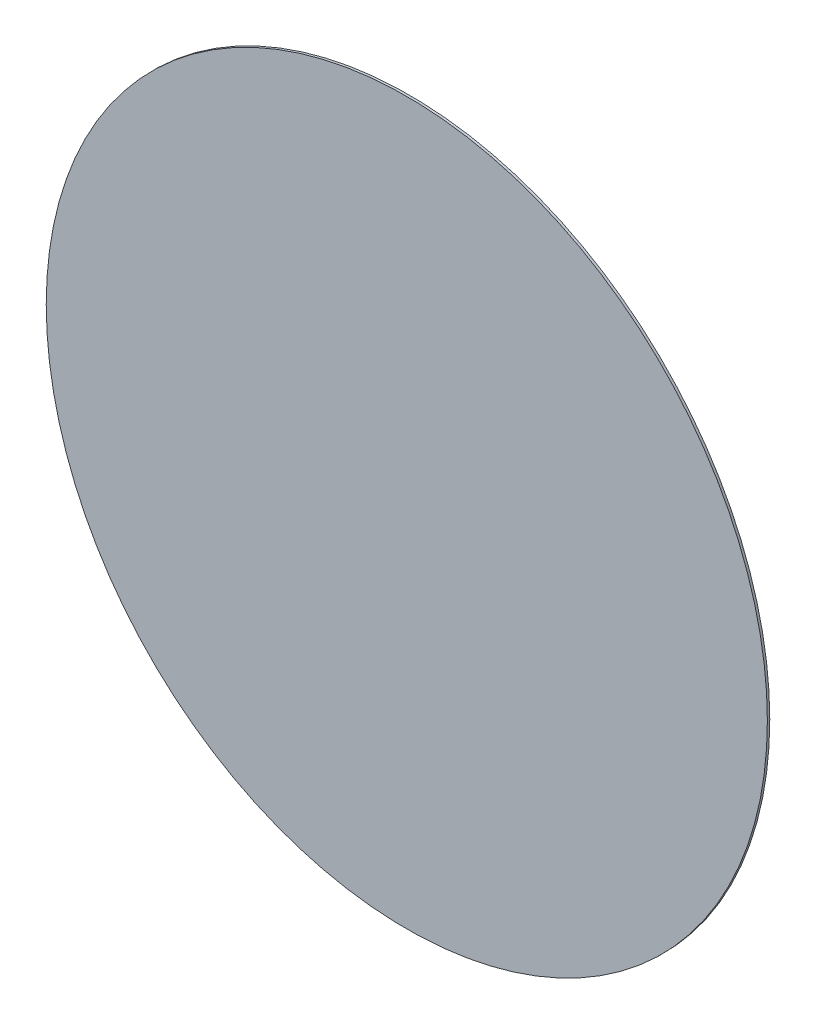
SolidWorks part; units mm, degrees
material "Stainless Steel (ferritic)"
ref_plane "Front" through (0, 0, 0) normal (0, 0, 1) x (1, 0, 0)
ref_plane "Top" through (0, 0, 0) normal (0, 1, 0) x (1, 0, 0)
ref_plane "Right" through (0, 0, 0) normal (1, 0, 0) x (0, 0, -1)
sketch "Sketch1" plane through (0, 0, 0) normal (0, 0, 1) x (1, 0, 0)
  circle A0 centre (0, 0) radius 30
extrude "Boss-Extrude1" add sketch "Sketch1" along normal blind 0.2
sketch "Sketch2" plane through (0, 0, 0) normal (0, 0, -1) x (-1, 0, 0)
  circle A0 centre (-14.7299, 12.3807) radius 0.5
sketch "Sketch3" plane through (0, 0, 0) normal (0, 0, -1) x (-1, 0, 0)
  line L0 (-15.2299, 12.3807) -> (-14.2299, 12.3807) construction
  circle A0 centre (-14.7299, 12.3807) radius 0.5 construction
ref_plane "Plane1" through (14.7299, 12.3807, 0) normal (-1, 0, 0) x (0, 0, 1)
sketch "Sketch4" plane through (14.7299, 12.3807, 0) normal (-1, 0, 0) x (0, 0, 1)
  line L0 (0, 0) -> (-3.5, 0)
  line L1 (0, 0.5) -> (0, -0.5) construction
  line L2 (-4, -0.5) -> (-4, -9.5)
  line L3 (-3.5, -10) -> (0, -10)
  arc A0 (-3.5, 0) -> (-4, -0.5) centre (-3.5, -0.5) ccw
  arc A1 (-3.5, -10) -> (-4, -9.5) centre (-3.5, -9.5) cw
  dimension "D1" = 0.5
sweep "Sweep1" add profiles "Sketch2" path "Sketch4"
